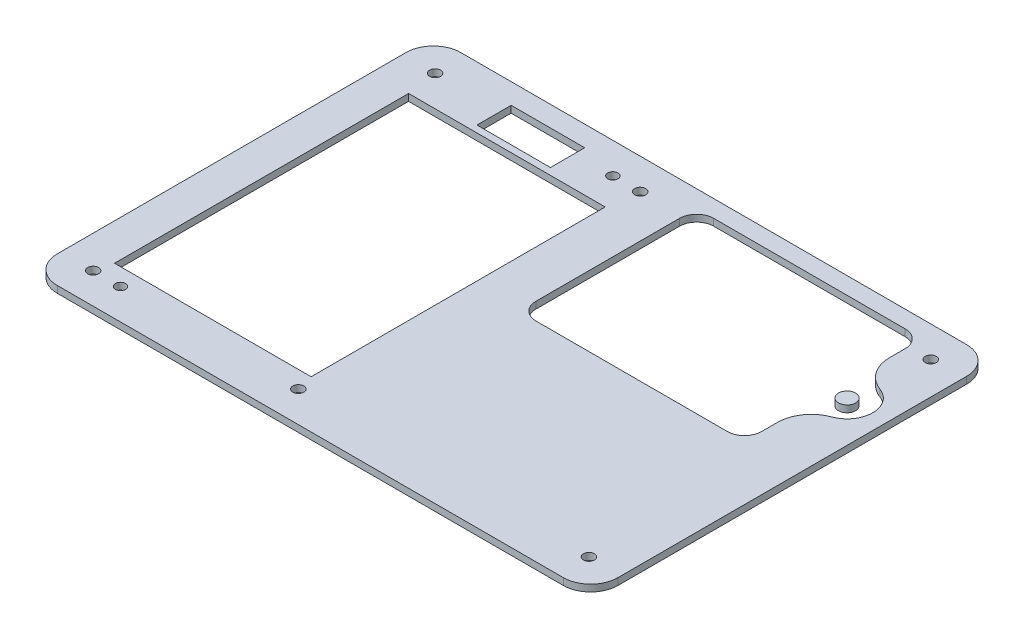
SolidWorks part; units mm, degrees
material "ABS"
ref_plane "Front Plane" through (0, 0, 0) normal (0, 0, 1) x (1, 0, 0)
ref_plane "Top Plane" through (0, 0, 0) normal (0, 1, 0) x (1, 0, 0)
ref_plane "Right Plane" through (0, 0, 0) normal (1, 0, 0) x (0, 0, -1)
sketch "Sketch1" plane through (0, 0, 0) normal (0, 1, 0) x (1, 0, 0)
  line L0 (0, 59) -> (0, 0) construction
  line L1 (-74, 59) -> (74, 59)
  line L2 (-82, 51) -> (-82, -51)
  line L3 (-74, -59) -> (74, -59)
  line L4 (82, 51) -> (82, -51)
  line L5 (0, 0) -> (0, -59) construction
  arc A0 (74, 59) -> (82, 51) centre (74, 51) cw
  arc A1 (74, -59) -> (82, -51) centre (74, -51) ccw
  arc A2 (-74, -59) -> (-82, -51) centre (-74, -51) cw
  arc A3 (-82, 51) -> (-74, 59) centre (-74, 51) cw
  dimension "D1" = 8
  dimension "D2" = 118
  dimension "D3" = 164
extrude "Boss-Extrude1" add sketch "Sketch1" along normal blind 2
sketch "Sketch2" plane through (0, 2, 0) normal (0, 1, 0) x (1, 0, 0)
  line L0 (-38.25, -50) -> (0, -50) construction
  line L1 (0, -50) -> (0, 0) construction
  line L2 (0, 0) -> (0, 50) construction
  line L3 (0, 50) -> (-38.25, 50) construction
  line L4 (-74, -59) -> (74, -59) construction
  line L15 (-82, 51) -> (-82, -51) construction
  line L23 (-71.25, 41) -> (-13.75, 41)
  line L24 (-71.25, 41) -> (-71.25, -45)
  line L25 (-71.25, -45) -> (-13.75, -45)
  line L26 (-13.75, 41) -> (-13.75, -45)
  circle A1 centre (-38.25, 50) radius 1.5 construction
  circle A2 centre (-38.25, -50) radius 1.5 construction
  dimension "D21" = 3
  dimension "D3" = 14
  dimension "D18" = 86
  dimension "D19" = 57.5
  dimension "D20" = 10.75
  dimension "D22" = 100
extrude "Cut-Extrude1" cut sketch "Sketch2" against normal through all
sketch "Sketch3" plane through (0, 2, 0) normal (0, 1, 0) x (1, 0, 0)
  line L0 (-71, 25) -> (-71, -25) construction
  line L1 (-74, 40) -> (-71, 40)
  line L2 (-74, 40) -> (-74, 25)
  line L3 (-74, 25) -> (-71, 25)
  line L4 (-71, 40) -> (-71, 25)
  line L5 (-74, -25) -> (-71, -25)
  line L6 (-74, -25) -> (-74, -40)
  line L7 (-74, -40) -> (-71, -40)
  line L8 (-71, -25) -> (-71, -40)
  line L9 (-71, 0) -> (0, 0) construction
  line L10 (-82, 51) -> (-82, -51) construction
  line L11 (0, 0) -> (0, 40) construction
  line L13 (71, -25) -> (71, -40)
  line L14 (74, -40) -> (71, -40)
  line L15 (74, -25) -> (74, -40)
  line L16 (74, -25) -> (71, -25)
  line L17 (71, 40) -> (71, 25)
  line L18 (74, 25) -> (71, 25)
  line L19 (74, 40) -> (74, 25)
  line L20 (74, 40) -> (71, 40)
  dimension "D1" = 3
  dimension "D2" = 15
  dimension "D3" = 8
  dimension "D4" = 50
  dimension "D5" = 40
extrude "Cut-Extrude2" [suppressed] cut sketch "Sketch3" against normal through all
sketch "Sketch4" [suppressed] plane through (0, 3, 0) normal (0, 1, 0) x (1, 0, 0)
  line L0 (-72.5, 0) -> (0, 0) construction
  line L1 (0, 0) -> (72.5, 0) construction
  line L2 (-72.5, 25) -> (-72.5, 0) construction
  line L3 (-74, 25) -> (-71, 25) construction
  circle A0 centre (-72.5, 0) radius 1.5
  circle A1 centre (72.5, 0) radius 1.5
  dimension "D1" = 3
extrude "Cut-Extrude3" [suppressed] cut sketch "Sketch4" against normal through all
sketch "Sketch5" plane through (0, 2, 0) normal (0, 1, 0) x (1, 0, 0)
  line L0 (-62, -55) -> (-62, -59)
  line L1 (-74, -59) -> (74, -59) construction
  line L2 (-62, -59) -> (-57, -59)
  line L3 (-57, -59) -> (-57, -55)
  line L4 (-82, 51) -> (-82, -51) construction
  arc A0 (-57, -55) -> (-62, -55) centre (-59.5, -55) ccw
  dimension "D1" = 5
  dimension "D2" = 4
  dimension "D3" = 20
extrude "Cut-Extrude4" [suppressed] cut sketch "Sketch5" against normal through all
sketch "Sketch6" [suppressed] plane through (0, 3, 0) normal (0, 1, 0) x (1, 0, 0)
  line L0 (-11.25, -48.5) -> (11.25, -48.5) construction
  line L1 (0, 0) -> (0, -48.5) construction
  circle A0 centre (-11.25, -48.5) radius 1.5
  circle A1 centre (11.25, -48.5) radius 1.5
  dimension "D1" = 3
extrude "Cut-Extrude5" [suppressed] cut sketch "Sketch6" against normal through all
ref_plane "Plane1" through (0, 0, 2) normal (0, 0, 1) x (1, 0, 0)
ref_plane "Plane2" through (-42.5, 0, 0) normal (-1, 0, 0) x (0, 0, 1)
sketch "Sketch7" plane through (0, 2, 0) normal (0, 1, 0) x (1, 0, 0)
  line L0 (0, 49) -> (0, 7)
  line L1 (61, 2) -> (5, 2)
  line L2 (66, 7) -> (66, 49) construction
  line L3 (61, 54) -> (5, 54)
  line L7 (0, 28) -> (66, 28) construction
  line L10 (70, 28) -> (66, 28) construction
  line L11 (66, 7) -> (66, 11.5607)
  line L12 (66, 44.4393) -> (66, 49)
  arc A0 (66, 7) -> (61, 2) centre (61, 7) cw
  arc A1 (5, 54) -> (0, 49) centre (5, 49) ccw
  arc A2 (5, 2) -> (0, 7) centre (5, 7) cw
  arc A3 (66, 49) -> (61, 54) centre (61, 49) ccw
  circle A8 centre (70, 28) radius 2.5
  arc A9 (72.5714, 20.9546) -> (72.5714, 35.0454) centre (70, 28) ccw
  arc A10 (66, 44.4393) -> (72.5714, 35.0454) centre (76, 44.4393) ccw
  arc A11 (72.5714, 20.9546) -> (66, 11.5607) centre (76, 11.5607) ccw
  point P32 (66, 34.3443)
  point P35 (66, 21.6557)
  dimension "D1" = 5
  dimension "D2" = 66
  dimension "D3" = 70
  dimension "D4" = 2
  dimension "D11" = 5
  dimension "D12" = 15
  dimension "D13" = 10
  dimension "D5" = 52
extrude "Cut-Extrude6" cut sketch "Sketch7" against normal through all
sketch "Sketch8" plane through (0, 2, 0) normal (0, 1, 0) x (1, 0, 0)
  line L0 (72.5, 50) -> (72.5, -50) construction
  line L2 (0, 0) -> (72.5, 0) construction
  circle A0 centre (72.5, -50) radius 1.6
  circle A2 centre (72.5, 50) radius 1.6
  dimension "D1" = 3.2
  dimension "D2" = 3.2
  dimension "D3" = 72.5
  dimension "D4" = 100
extrude "Cut-Extrude7" cut sketch "Sketch8" against normal through all
mirror "Mirror1" about plane through (0, 0, 0) normal (1, 0, 0) of "Cut-Extrude7"
sketch "Sketch9" plane through (0, 2, 0) normal (0, 1, 0) x (1, 0, 0)
  line L0 (0, 0) -> (0, -24) construction
  line L1 (0, -37) -> (7, -37)
  line L2 (0, -37) -> (0, -24)
  line L3 (0, -24) -> (7, -24)
  line L4 (7, -37) -> (7, -24)
  line L5 (0, -37) -> (0, -59) construction
  line L6 (-74, -59) -> (74, -59) construction
  dimension "D1" = 7
  dimension "D2" = 13
  dimension "D3" = 24
extrude "Cut-Extrude8" [suppressed] cut sketch "Sketch9" against normal through all
sketch "Sketch10" plane through (0, 2, 0) normal (0, 1, 0) x (1, 0, 0)
  line L0 (-72.5, -50) -> (-12.5, -50) construction
  line L1 (-12.5, -50) -> (-12.5, 50) construction
  line L2 (-12.5, 50) -> (-72.5, 50) construction
  line L3 (-42.5, -2) -> (-42.5, -50) construction
  line L4 (-1.1, -2) -> (1.1, -2) construction
  line L5 (-42.5, 1.1) -> (-42.5, -1.1) construction
  circle A0 centre (-12.5, -50) radius 1.6
  circle A1 centre (-12.5, 50) radius 1.6
  circle A2 centre (-72.5, -50) radius 1.6 construction
extrude "Cut-Extrude9" cut sketch "Sketch10" against normal through all
sketch "Sketch11" plane through (0, 0, 0) normal (0, -1, 0) x (-1, 0, 0)
  line L0 (42.5, 43) -> (42.5, -45) construction
  line L1 (31.75, 43) -> (53.25, 43)
  line L2 (31.75, 43) -> (31.75, 53)
  line L3 (31.75, 53) -> (53.25, 53)
  line L4 (53.25, 43) -> (53.25, 53)
  line L5 (71.25, -45) -> (13.75, -45) construction
  line L6 (0, 0) -> (42.5, 0) construction
  line L7 (31.75, 48) -> (42.5, 48) construction
  line L8 (42.5, 48) -> (42.5, 43) construction
  dimension "D1" = 10
  dimension "D2" = 21.5
  dimension "D3" = 48
extrude "Cut-Extrude10" cut sketch "Sketch11" against normal through all
sketch "Sketch12" plane through (0, 2, 0) normal (0, 1, 0) x (1, 0, 0)
  line L0 (-20.5, 50) -> (-20.5, -2) construction
  line L1 (-1.1, -2) -> (1.1, -2) construction
  line L2 (-20.5, -2) -> (-42.5, -2) construction
  line L3 (-72.5, -50) -> (-64.5, -50) construction
  line L4 (-42.5, 1.1) -> (-42.5, -1.1) construction
  line L5 (-42.5, -2) -> (-64.5, -2) construction
  line L6 (-64.5, -2) -> (-64.5, -50) construction
  line L7 (-20.5, 50) -> (-12.5, 50) construction
  circle A0 centre (-64.5, -50) radius 1.5
  circle A1 centre (-20.5, 50) radius 1.5
  dimension "D1" = 3
  dimension "D2" = 44
  dimension "D3" = 22
extrude "Cut-Extrude11" cut sketch "Sketch12" against normal through all
